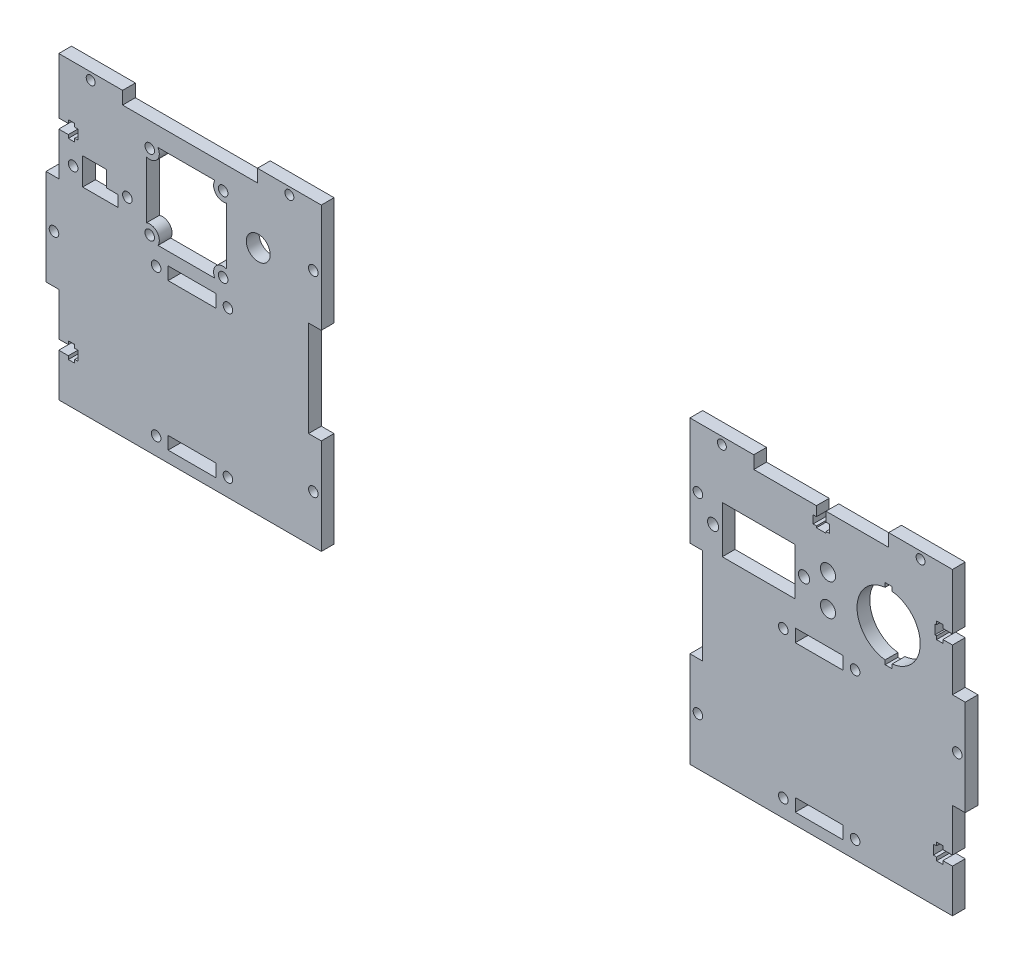
SolidWorks part; units mm, degrees
ref_plane "Спереди" through (0, 0, 0) normal (0, 0, 1) x (1, 0, 0)
ref_plane "Сверху" through (0, 0, 0) normal (0, 1, 0) x (1, 0, 0)
ref_plane "Справа" through (0, 0, 0) normal (1, 0, 0) x (0, 0, -1)
sketch "Эскиз1" plane through (0, 0, 0) normal (0, 0, 1) x (1, 0, 0)
  line L1 (-140, -45) -> (140, -45)
  line L2 (-140, -45) -> (-140, 45)
  line L3 (-140, 45) -> (140, 45)
  line L4 (140, -45) -> (140, 45)
  line L5 (-140, -45) -> (140, 45) construction
  line L6 (-140, 45) -> (140, -45) construction
  line L7 (-105.75, -37.5) -> (-90.75, -37.5)
  line L8 (-105.75, -37.5) -> (-105.75, -41.5)
  line L9 (-105.75, -41.5) -> (-90.75, -41.5)
  line L10 (-90.75, -37.5) -> (-90.75, -41.5)
  line L11 (-105.75, -37.5) -> (-90.75, -41.5) construction
  line L12 (-105.75, -41.5) -> (-90.75, -37.5) construction
  line L13 (-105.75, 4.5) -> (-90.75, 4.5)
  line L14 (-105.75, 4.5) -> (-105.75, 8.5)
  line L15 (-105.75, 8.5) -> (-90.75, 8.5)
  line L16 (-90.75, 4.5) -> (-90.75, 8.5)
  line L17 (-105.75, 4.5) -> (-90.75, 8.5) construction
  line L18 (-105.75, 8.5) -> (-90.75, 4.5) construction
  line L19 (-108.25, -33.25) -> (-88.25, -33.25)
  line L20 (-108.25, -33.25) -> (-108.25, -2.75)
  line L21 (-108.25, -2.75) -> (-88.25, -2.75)
  line L22 (-88.25, -33.25) -> (-88.25, -2.75)
  line L23 (-108.25, -33.25) -> (-88.25, -2.75) construction
  line L24 (-108.25, -2.75) -> (-88.25, -33.25) construction
  line L34 (0, -55) -> (0, 55) construction
  line L35 (108.25, -2.75) -> (88.25, -33.25) construction
  line L36 (108.25, -33.25) -> (88.25, -2.75) construction
  line L37 (105.75, 8.5) -> (90.75, 4.5) construction
  line L38 (105.75, 4.5) -> (90.75, 8.5) construction
  line L39 (105.75, -41.5) -> (90.75, -37.5) construction
  line L40 (105.75, -37.5) -> (90.75, -41.5) construction
  line L41 (88.25, -33.25) -> (88.25, -2.75)
  line L42 (108.25, -2.75) -> (88.25, -2.75)
  line L43 (108.25, -33.25) -> (108.25, -2.75)
  line L44 (108.25, -33.25) -> (88.25, -33.25)
  line L45 (90.75, 4.5) -> (90.75, 8.5)
  line L46 (105.75, 8.5) -> (90.75, 8.5)
  line L47 (105.75, 4.5) -> (105.75, 8.5)
  line L48 (105.75, 4.5) -> (90.75, 4.5)
  line L49 (90.75, -37.5) -> (90.75, -41.5)
  line L50 (105.75, -41.5) -> (90.75, -41.5)
  line L51 (105.75, -37.5) -> (105.75, -41.5)
  line L52 (105.75, -37.5) -> (90.75, -37.5)
  line L53 (-109.5, 6.5) -> (-87, 6.5) construction
  line L54 (-109.5, -39.5) -> (-87, -39.5) construction
  line L64 (-61.75, -15) -> (-57.75, -15) construction
  line L66 (-135.5, 37.5) -> (-118.5, 37.5) construction
  line L75 (-140, -45) -> (140, -45) construction
  line L77 (118.9, 12.6) -> (121.1, 12.6)
  line L89 (140, -15) -> (144, -15) construction
  line L90 (144, -15) -> (144, 15) construction
  line L91 (144, 15) -> (140, 15) construction
  line L93 (118.9, 12.6) -> (118.9, 34.9)
  line L96 (118.9, 34.9) -> (121.1, 34.9)
  line L105 (98.875, 39) -> (98.875, 8.5) construction
  line L108 (-61.75, 15) -> (-61.75, -15) construction
  line L124 (-57.75, 15) -> (-61.75, 15) construction
  line L163 (-140, 15) -> (-144, 15) construction
  line L164 (-144, 15) -> (-144, -15) construction
  line L165 (-144, -15) -> (-140, -15) construction
  line L167 (121.1, 12.6) -> (121.1, 34.9)
  line L190 (-140, -45) -> (140, -45)
  line L204 (140, -15) -> (144, -15)
  line L205 (144, -15) -> (144, 15)
  line L206 (144, 15) -> (140, 15)
  line L278 (-140, 15) -> (-144, 15)
  line L279 (-144, 15) -> (-144, -15)
  line L280 (-144, -15) -> (-140, -15)
  line L285 (-137, -32.55) -> (-137, -31.5) construction
  line L286 (-137, -31.5) -> (-140, -31.5) construction
  line L287 (-137, -28.5) -> (-137, -27.45) construction
  line L288 (-140, -28.5) -> (-137, -28.5) construction
  line L289 (-57.75, 45) -> (-57.75, -45)
  line L292 (-57.75, -15) -> (-57.75, 15) construction
  line L293 (57.75, 45) -> (57.75, -45)
  line L297 (-57.75, -15) -> (-57.75, 15) construction
  line L298 (-61.75, -15) -> (-57.75, -15)
  line L299 (-61.75, 15) -> (-61.75, -15)
  line L300 (-57.75, 15) -> (-61.75, 15)
  line L301 (-57.75, -15) -> (-57.75, 15)
  line L302 (0, -159.5373) -> (0, 159.5373) construction
  line L303 (57.75, -15) -> (57.75, 15)
  line L304 (57.75, 15) -> (61.75, 15)
  line L305 (61.75, 15) -> (61.75, -15)
  line L306 (61.75, -15) -> (57.75, -15)
  line L307 (-60.25, 15) -> (-60.25, 45) construction
  line L308 (55, 0) -> (-55, 0) construction
  line L309 (-111.5, 37.5) -> (-88.5, 37.5) construction
  line L310 (-106.25, 40) -> (-93.75, 40)
  line L311 (-106.25, 40) -> (-106.25, 36)
  line L312 (-106.25, 36) -> (-93.75, 36)
  line L313 (-93.75, 40) -> (-93.75, 36)
  line L314 (-140, 45) -> (-140, 49) construction
  line L315 (-140, 45) -> (-120, 45) construction
  line L316 (-120, 45) -> (-120, 49) construction
  line L317 (-140, 49) -> (-120, 49) construction
  line L318 (140, 45) -> (120, 45) construction
  line L319 (140, 45) -> (140, 49) construction
  line L320 (140, 49) -> (120, 49) construction
  line L321 (120, 45) -> (120, 49) construction
  line L322 (-140, 45) -> (-140, 49)
  line L323 (-140, 45) -> (-120, 45)
  line L324 (-120, 45) -> (-120, 49)
  line L325 (-140, 49) -> (-120, 49)
  line L326 (140, 45) -> (120, 45)
  line L327 (140, 45) -> (140, 49)
  line L328 (140, 49) -> (120, 49)
  line L329 (120, 45) -> (120, 49)
  line L330 (77.75, 45) -> (77.75, 49)
  line L331 (-57.75, 45) -> (-77.75, 45)
  line L332 (-57.75, 45) -> (-57.75, 49)
  line L333 (-57.75, 49) -> (-77.75, 49)
  line L334 (-77.75, 45) -> (-77.75, 49)
  line L335 (57.75, 49) -> (77.75, 49)
  line L336 (57.75, 45) -> (57.75, 49)
  line L337 (57.75, 45) -> (77.75, 45)
  line L338 (77.75, 49) -> (120, 49) construction
  line L339 (97.375, 45) -> (100.375, 45)
  line L340 (97.375, 45) -> (97.375, 39)
  line L341 (97.375, 39) -> (100.375, 39)
  line L342 (100.375, 45) -> (100.375, 39)
  line L343 (67.875, 16.375) -> (90.625, 16.375)
  line L344 (96.325, 39.5) -> (101.425, 39.5)
  line L345 (96.325, 39.5) -> (96.325, 42)
  line L346 (96.325, 42) -> (101.425, 42)
  line L347 (101.425, 39.5) -> (101.425, 42)
  line L348 (96.325, 39.5) -> (101.425, 42) construction
  line L349 (96.325, 42) -> (101.425, 39.5) construction
  line L350 (67.875, 16.375) -> (67.875, 31.125)
  line L351 (67.875, 31.125) -> (90.625, 31.125)
  line L352 (90.625, 16.375) -> (90.625, 31.125)
  line L353 (67.875, 16.375) -> (90.625, 31.125) construction
  line L354 (67.875, 31.125) -> (90.625, 16.375) construction
  line L355 (65, 23.75) -> (93.5, 23.75) construction
  line L356 (-135, -27.45) -> (-135, -28.5) construction
  line L357 (-137, -27.45) -> (-135, -27.45) construction
  line L358 (-135, -31.5) -> (-135, -32.55) construction
  line L359 (-135, -32.55) -> (-137, -32.55) construction
  line L360 (-134, -28.5) -> (-134, -31.5) construction
  line L361 (-134, -31.5) -> (-135, -31.5) construction
  line L362 (-135, -28.5) -> (-134, -28.5) construction
  line L363 (-137, 27.45) -> (-137, 28.5) construction
  line L364 (-137, 28.5) -> (-140, 28.5) construction
  line L365 (-135, 27.45) -> (-137, 27.45) construction
  line L366 (-135, 28.5) -> (-135, 27.45) construction
  line L367 (-134, 28.5) -> (-135, 28.5) construction
  line L368 (-134, 31.5) -> (-134, 28.5) construction
  line L369 (-135, 31.5) -> (-134, 31.5) construction
  line L370 (-135, 32.55) -> (-135, 31.5) construction
  line L371 (-137, 32.55) -> (-135, 32.55) construction
  line L372 (-137, 31.5) -> (-137, 32.55) construction
  line L373 (-140, 31.5) -> (-137, 31.5) construction
  line L374 (-137, -32.55) -> (-137, -31.5)
  line L375 (-137, -31.5) -> (-140, -31.5)
  line L376 (-137, -28.5) -> (-137, -27.45)
  line L377 (-140, -28.5) -> (-137, -28.5)
  line L378 (-135, -27.45) -> (-135, -28.5)
  line L379 (-137, -27.45) -> (-135, -27.45)
  line L380 (-135, -31.5) -> (-135, -32.55)
  line L381 (-135, -32.55) -> (-137, -32.55)
  line L382 (-134, -28.5) -> (-134, -31.5)
  line L383 (-134, -31.5) -> (-135, -31.5)
  line L384 (-135, -28.5) -> (-134, -28.5)
  line L385 (-137, 27.45) -> (-137, 28.5)
  line L386 (-137, 28.5) -> (-140, 28.5)
  line L387 (-135, 27.45) -> (-137, 27.45)
  line L388 (-135, 28.5) -> (-135, 27.45)
  line L389 (-134, 28.5) -> (-135, 28.5)
  line L390 (-134, 31.5) -> (-134, 28.5)
  line L391 (-135, 31.5) -> (-134, 31.5)
  line L392 (-135, 32.55) -> (-135, 31.5)
  line L393 (-137, 32.55) -> (-135, 32.55)
  line L394 (-137, 31.5) -> (-137, 32.55)
  line L395 (-140, 31.5) -> (-137, 31.5)
  line L396 (135, -28.5) -> (134, -28.5)
  line L397 (134, -31.5) -> (135, -31.5)
  line L398 (134, -28.5) -> (134, -31.5)
  line L399 (135, -32.55) -> (137, -32.55)
  line L400 (135, -31.5) -> (135, -32.55)
  line L401 (137, -27.45) -> (135, -27.45)
  line L402 (135, -27.45) -> (135, -28.5)
  line L403 (140, -28.5) -> (137, -28.5)
  line L404 (137, -28.5) -> (137, -27.45)
  line L405 (137, -31.5) -> (140, -31.5)
  line L406 (137, -32.55) -> (137, -31.5)
  line L407 (140, 31.5) -> (137, 31.5)
  line L408 (137, 31.5) -> (137, 32.55)
  line L409 (137, 32.55) -> (135, 32.55)
  line L410 (135, 32.55) -> (135, 31.5)
  line L411 (135, 31.5) -> (134, 31.5)
  line L412 (134, 31.5) -> (134, 28.5)
  line L413 (134, 28.5) -> (135, 28.5)
  line L414 (135, 28.5) -> (135, 27.45)
  line L415 (135, 27.45) -> (137, 27.45)
  line L416 (137, 28.5) -> (140, 28.5)
  line L417 (137, 27.45) -> (137, 28.5)
  line L418 (101, 28.75) -> (101, 18.75) construction
  line L419 (134.5, 31.5) -> (134.5, 28.5)
  line L420 (108.85, 22.65) -> (131.15, 22.65)
  line L421 (108.85, 22.65) -> (108.85, 24.85)
  line L422 (108.85, 24.85) -> (131.15, 24.85)
  line L423 (131.15, 22.65) -> (131.15, 24.85)
  line L424 (108.85, 22.65) -> (131.15, 24.85) construction
  line L425 (108.85, 24.85) -> (131.15, 22.65) construction
  line L426 (-112.5, 34.6716) -> (-112.5, 16.8284)
  line L427 (-108.9216, 12.4665) -> (-91.0784, 12.4665)
  line L428 (-87.5, 16.8284) -> (-87.5, 34.6716)
  line L429 (-91.0784, 39.0335) -> (-108.9216, 39.0335)
  line L430 (118.9, 12.6) -> (121.1, 34.9) construction
  line L431 (118.9, 34.9) -> (121.1, 12.6) construction
  line L432 (-132.5, 16.5) -> (-121.5, 16.5)
  line L433 (-132.5, 16.5) -> (-132.5, 25)
  line L434 (-132.5, 25) -> (-121.5, 25)
  line L435 (-121.5, 16.5) -> (-121.5, 25)
  line L436 (-132.5, 16.5) -> (-121.5, 25) construction
  line L437 (-132.5, 25) -> (-121.5, 16.5) construction
  line L438 (-121.5, 25) -> (-125, 25)
  line L439 (-121.5, 25) -> (-121.5, 20)
  line L440 (-121.5, 20) -> (-125, 20)
  line L441 (-125, 25) -> (-125, 20)
  circle A9 centre (-98.25, 19) radius 9.25 construction
  circle A14 centre (-141.5, 0) radius 1.5
  circle A16 centre (141.5, 0) radius 1.5
  circle A26 centre (-87, 6.5) radius 1.5
  circle A27 centre (-109.5, 6.5) radius 1.5
  circle A28 centre (-109.5, -39.5) radius 1.5
  circle A29 centre (-87, -39.5) radius 1.5
  circle A30 centre (87, -39.5) radius 1.5
  circle A31 centre (109.5, -39.5) radius 1.5
  circle A32 centre (109.5, 6.5) radius 1.5
  circle A33 centre (87, 6.5) radius 1.5
  circle A34 centre (-60.25, 30) radius 1.5
  circle A35 centre (-60.25, -30) radius 1.5
  circle A36 centre (60.25, -30) radius 1.5
  circle A37 centre (60.25, 30) radius 1.5
  circle A38 centre (-77.5, 27.5) radius 3.75
  circle A40 centre (-88.5, 37.5) radius 1.5
  circle A41 centre (-111.5, 37.5) radius 1.5
  circle A42 centre (-111.5, 14) radius 1.5
  circle A43 centre (-88.5, 14) radius 1.5
  circle A44 centre (-130, 46.75) radius 1.4 construction
  circle A45 centre (130, 46.75) radius 1.4 construction
  circle A46 centre (-130, 46.75) radius 1.4
  circle A47 centre (130, 46.75) radius 1.4
  circle A48 centre (-67.75, 46.75) radius 1.4
  circle A49 centre (67.75, 46.75) radius 1.4
  circle A50 centre (65, 23.75) radius 1.75
  circle A51 centre (93.5, 23.75) radius 1.75
  circle A52 centre (101, 18.75) radius 2.375
  circle A53 centre (101, 28.75) radius 2.375
  circle A54 centre (120, 23.75) radius 9.9
  circle A55 centre (-111.5, 37.5) radius 3
  circle A56 centre (-88.5, 37.5) radius 3
  circle A57 centre (-88.5, 14) radius 3
  circle A58 centre (-111.5, 14) radius 3
  circle A59 centre (-135.5, 20.75) radius 1.5
  circle A60 centre (-118.5, 20.75) radius 1.5
  circle A61 centre (-135.5, 37.5) radius 1.5
  circle A62 centre (-118.5, 37.5) radius 1.5
  circle A65 centre (-127, 37.5) radius 4.75
  point P0 (0, 0)
  point P5 (-98.25, -39.5)
  point P11 (-98.25, 6.5)
  point P16 (-98.25, -18)
  point P28 (98.25, 19)
  point P40 (-144, 0)
  point P54 (-98.25, 6.5)
  point P58 (-98.25, -2.75)
  point P63 (98.25, -18)
  point P64 (98.25, 6.5)
  point P65 (98.25, -39.5)
  point P66 (-98.25, -39.5)
  point P82 (101, 23.75)
  point P155 (-100, 36)
  point P157 (-100, 37.5)
  point P173 (98.875, 49)
  point P175 (98.875, 39)
  point P177 (-67.75, 49)
  point P187 (98.875, 40.75)
  point P192 (79.25, 23.75)
  point P199 (98.875, 23.75)
  point P204 (79.25, 23.75)
  point P217 (110.1, 23.75)
  point P246 (-127, 20.75)
  point P262 (-127, 37.5)
  dimension "D10" = 3
  dimension "D23" = 2
  dimension "D24" = 23
  dimension "D25" = 18.5
  dimension "D30" = 7.5
  dimension "D32" = 19.8
  dimension "D11" = 3
  dimension "D15" = 3
  dimension "D17" = 7.5
  dimension "D19" = 3
  dimension "D43" = 3.5
  dimension "D45" = 4.75
  dimension "D48" = 20
  dimension "D59" = 3
  dimension "D64" = 9.5
  dimension "D1" = 280
  dimension "D2" = 90
  dimension "D3" = 3.5
  dimension "D4" = 15
  dimension "D5" = 4
  dimension "D6" = 42
  dimension "D7" = 11.75
  dimension "D8" = 30.5
  dimension "D9" = 20
  dimension "D12" = 2.5
  dimension "D13" = 6
  dimension "D14" = 2.5
  dimension "D16" = 10
  dimension "D18" = 17.5
  dimension "D20" = 64
  dimension "D21" = 98.25
  dimension "D22" = 22.5
  dimension "D26" = 22.5
  dimension "D27" = 2
  dimension "D28" = 98.25
  dimension "D29" = 23.5
  dimension "D31" = 28.5
  dimension "D33" = 12.5
  dimension "D34" = 4
  dimension "D35" = 2.5
  dimension "D36" = 3
  dimension "D37" = 2.5
  dimension "D38" = 5.1
  dimension "D39" = 3
  dimension "D40" = 22.75
  dimension "D41" = 14.75
  dimension "D42" = 17.5
  dimension "D44" = 28.5
  dimension "D46" = 10
  dimension "D47" = 7.5
  dimension "D49" = 2.2
  dimension "D50" = 1.25
  dimension "D52" = 25
  dimension "D53" = 11
  dimension "D54" = 8.5
  dimension "D55" = 7.5
  dimension "D56" = 5
  dimension "D57" = 13
  dimension "D61" = 20
  dimension "D62" = 17
  dimension "D63" = 7.5
  dimension "D51" = 1.5
extrude "Бобышка-Вытянуть1" add sketch "Эскиз1" along normal blind 4
